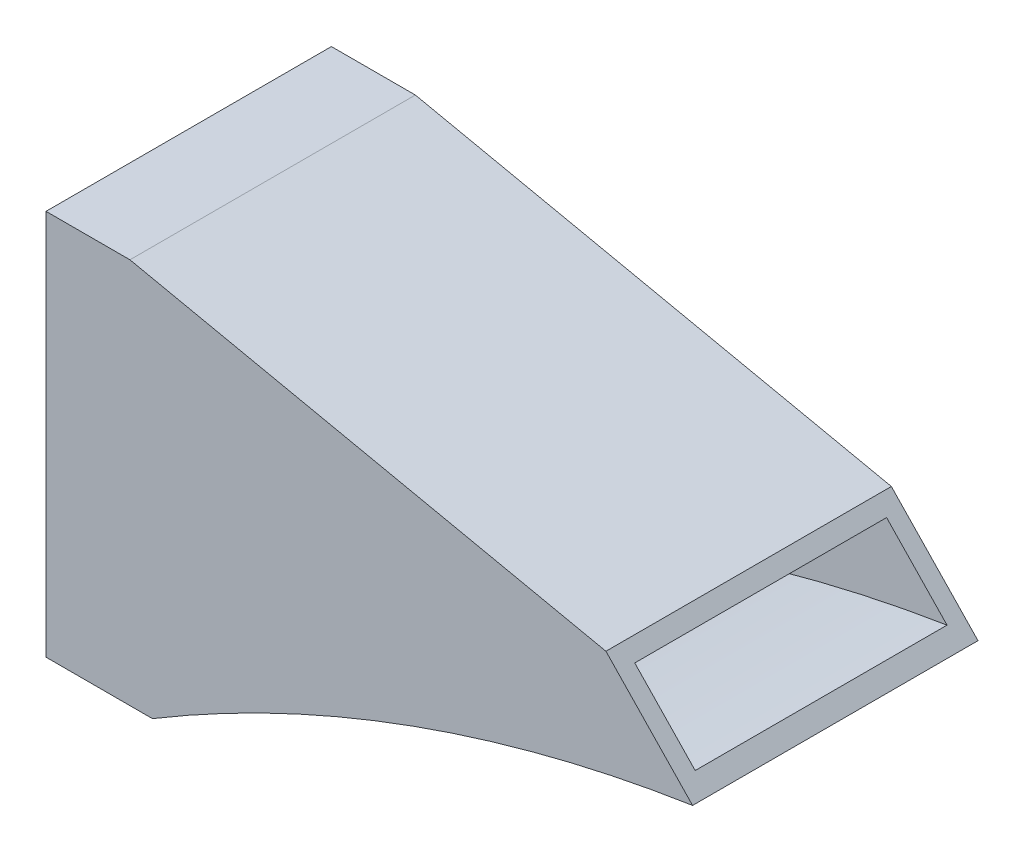
SolidWorks part; units mm, degrees
ref_plane "Front Plane" through (0, 0, 0) normal (0, 0, 1) x (1, 0, 0)
ref_plane "Top Plane" through (0, 0, 0) normal (0, 1, 0) x (1, 0, 0)
ref_plane "Right Plane" through (0, 0, 0) normal (1, 0, 0) x (0, 0, -1)
sketch "Sketch1" plane through (0, 0, 0) normal (0, 0, 1) x (1, 0, 0)
  line L0 (22.4, 5.7) -> (22.4, 28.7)
  line L1 (22.4, 28.7) -> (27.4, 28.7)
  line L2 (27.4, 28.7) -> (55.753, 22.6836)
  line L3 (55.753, 22.6836) -> (60.9146, 17.3096)
  line L4 (22.4, 5.7) -> (28.7393, 5.7)
  line L5 (85.4488, 17.4701) -> (83.6998, 17.8412) construction
  line L6 (83.6998, 17.8412) -> (-21.7307, 40.213) construction
  arc A0 (60.9146, 17.3096) -> (28.7393, 5.7) centre (74.3215, -70.2378) ccw
  dimension "D7" = 88.568
  dimension "D1" = 5
  dimension "D2" = 6.3393
  dimension "D3" = 23
  dimension "D4" = 38.5146
  dimension "D5" = 33.353
  dimension "D6" = 5.3741
  dimension "D8" = 22.4
  dimension "D9" = 5.7
extrude "Boss-Extrude3" add sketch "Sketch1" against normal blind 17 from offset 1
sketch "Sketch2" plane through (0, 0, 1) normal (0, 0, 1) x (1, 0, 0)
  line L0 (22.4, 6.7) -> (28.463, 6.7)
  line L2 (22.4, 6.7) -> (22.4, 27.7)
  line L3 (22.4, 27.7) -> (27.2951, 27.7)
  line L4 (60.0699, 18.1891) -> (56.4693, 21.9379)
  line L5 (60.9146, 17.3096) -> (55.753, 22.6836) construction
  line L6 (56.4693, 21.9379) -> (54.4498, 21.9379)
  line L7 (24.4, 27.7) -> (-0.0106, 27.7) construction
  line L9 (22.4, 28.7) -> (22.4, 5.7) construction
  line L10 (54.4498, 21.9379) -> (27.2951, 27.7)
  line L11 (55.753, 22.6836) -> (27.4, 28.7) construction
  line L12 (22.4, 5.7) -> (28.7393, 5.7) construction
  arc A0 (60.0699, 18.1891) -> (28.463, 6.7) centre (74.3215, -70.2378) ccw
  arc A3 (60.9146, 17.3096) -> (28.7393, 5.7) centre (74.3215, -70.2378) ccw construction
  dimension "D4" = 1
  dimension "D1" = 0
  dimension "D2" = 1
  dimension "D3" = 1
  dimension "D5" = 0.7457
extrude "Cut-Extrude1" cut sketch "Sketch2" against normal blind 15 from offset 1
